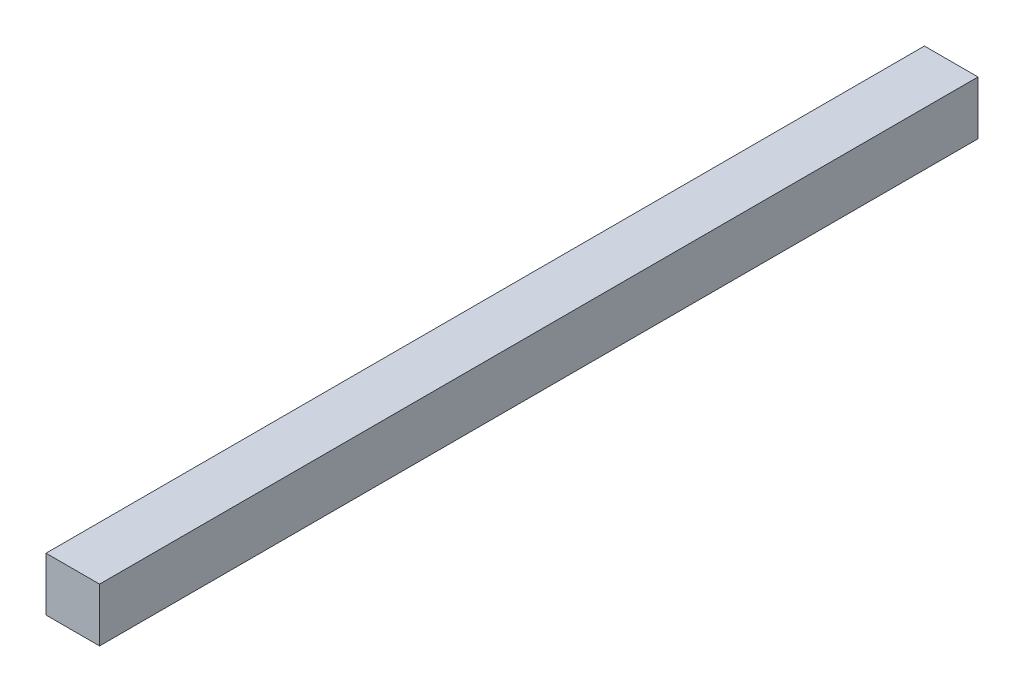
SolidWorks part; units mm, degrees
ref_plane "Plan de face" through (0, 0, 0) normal (0, 0, 1) x (1, 0, 0)
ref_plane "Plan de dessus" through (0, 0, 0) normal (0, 1, 0) x (1, 0, 0)
ref_plane "Plan de droite" through (0, 0, 0) normal (1, 0, 0) x (0, 0, -1)
sketch "Esquisse1" plane through (0, 0, 0) normal (0, 0, 1) x (1, 0, 0)
  line L1 (0, 0) -> (10, 0)
  line L2 (0, 0) -> (0, 10)
  line L3 (0, 10) -> (10, 10)
  line L4 (10, 0) -> (10, 10)
  dimension "D1" = 10
  dimension "D2" = 10
extrude "Boss.-Extru.1" add sketch "Esquisse1" along normal blind 164
